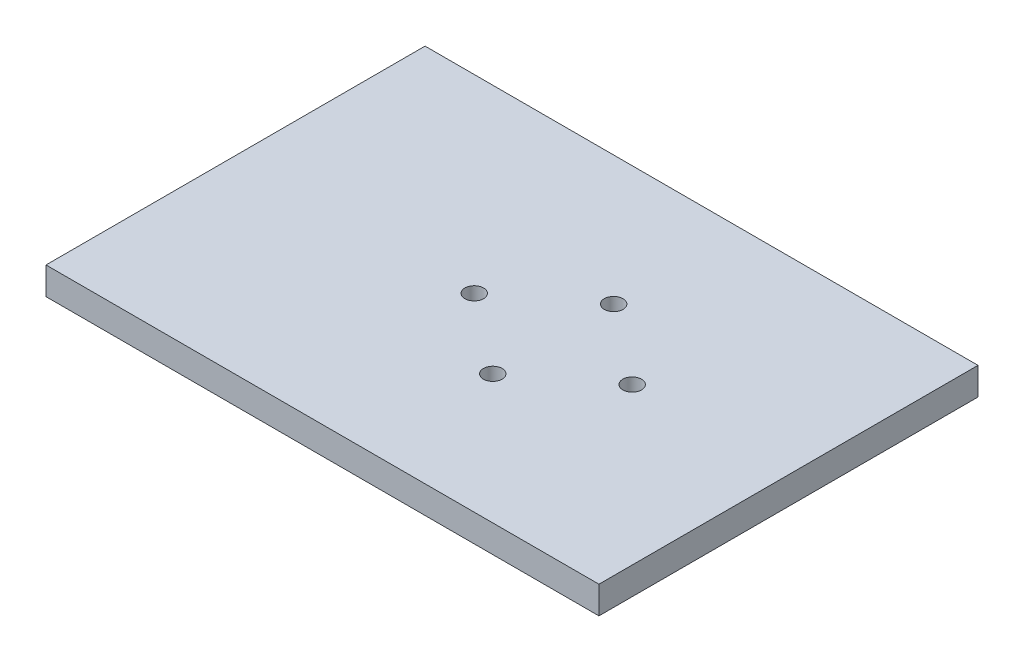
SolidWorks part; units mm, degrees
material "1060 Alloy"
ref_plane "Front Plane" through (0, 0, 0) normal (0, 0, 1) x (1, 0, 0)
ref_plane "Top Plane" through (0, 0, 0) normal (0, 1, 0) x (1, 0, 0)
ref_plane "Right Plane" through (0, 0, 0) normal (1, 0, 0) x (0, 0, -1)
sketch "Sketch1" plane through (0, 0, 0) normal (0, 1, 0) x (1, 0, 0)
  line L59 (-57.825, -46.5) -> (57.825, -46.5) construction
  line L79 (-9.5745, 0) -> (9.5745, 0) construction
  line L80 (0, 7.6993) -> (0, -7.6993) construction
  line L81 (-57.825, -46.5) -> (-57.825, 46.5) construction
  line L82 (-57.825, 46.5) -> (57.825, 46.5) construction
  line L83 (57.825, -46.5) -> (57.825, 46.5) construction
  line L84 (-57.825, -46.5) -> (57.825, 46.5) construction
  line L85 (-57.825, 46.5) -> (57.825, -46.5) construction
  line L86 (42.825, -34.5) -> (-57.825, -34.5)
  line L87 (42.825, -34.5) -> (42.825, 34.5)
  line L88 (42.825, 34.5) -> (-57.825, 34.5)
  line L89 (-57.825, -34.5) -> (-57.825, 34.5)
  circle A1 centre (0, 11) radius 1.7
  circle A3 centre (-14.375, 0) radius 1.7
  circle A4 centre (0, -11) radius 1.7
  circle A5 centre (14.375, 0) radius 1.7
  point P6 (0, 0)
  dimension "D6" = 3.4
  dimension "D8" = 3.4
  dimension "D1" = 115.65
  dimension "D2" = 93
  dimension "D5" = 28.75
  dimension "D7" = 22
  dimension "D9" = 12
  dimension "D3" = 12
  dimension "D4" = 15
extrude "Boss-Extrude1" add sketch "Sketch1" along normal blind 5
equation "\"L1L\"=500"
equation "\"L1Thick\"=6.35"
equation "\"Harm-Drive-Outer\"=74.5"
equation "\"L1-Spacing\"=115.65"
equation "\"L-Bracket-HoleToWall\"=12.5"
equation "\"L-Bracket-HoleToSide\"=11"
equation "\"Bracket-Hole-D\"=6.8"
equation "\"D1@Sketch1\"=\"L1-Spacing\""
